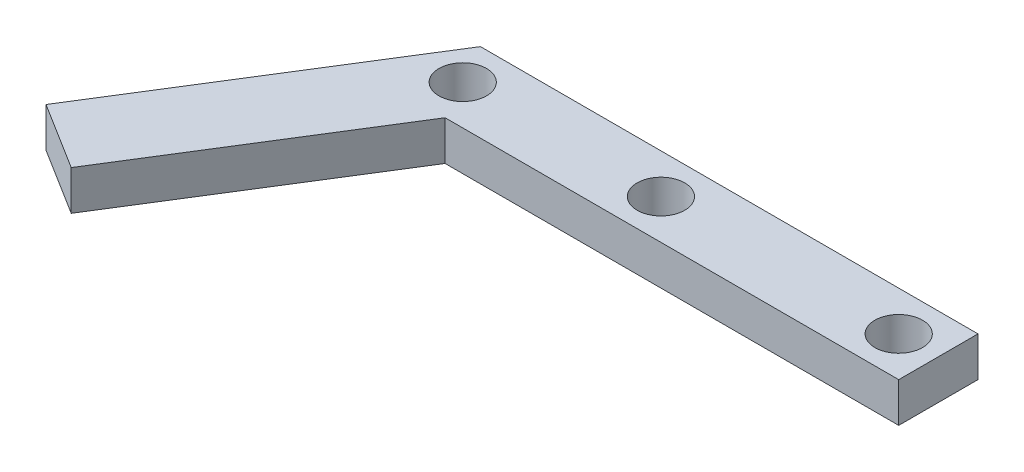
SolidWorks part; units mm, degrees
ref_plane "Front Plane" through (0, 0, 0) normal (0, 0, 1) x (1, 0, 0)
ref_plane "Top Plane" through (0, 0, 0) normal (0, 1, 0) x (1, 0, 0)
ref_plane "Right Plane" through (0, 0, 0) normal (1, 0, 0) x (0, 0, -1)
sketch "Sketch1" plane through (0, 0, 0) normal (0, 1, 0) x (1, 0, 0)
  line L0 (0, 0) -> (16.9574, 27.1375) construction
  line L1 (16.9574, 27.1375) -> (71.9574, 27.1375) construction
  line L2 (0, 0) -> (-2.6496, -4.2402) construction
  line L3 (1.5906, -6.8898) -> (-6.8898, -1.5906)
  line L4 (-6.8898, -1.5906) -> (14.1859, 32.1375)
  line L5 (1.5906, -6.8898) -> (19.729, 22.1375)
  line L6 (71.9574, 27.1375) -> (76.9574, 27.1375) construction
  line L7 (76.9574, 22.1375) -> (76.9574, 32.1375)
  line L8 (76.9574, 22.1375) -> (19.729, 22.1375)
  line L9 (76.9574, 32.1375) -> (14.1859, 32.1375)
  circle A1 centre (16.9574, 27.1375) radius 3
  circle A2 centre (71.9574, 27.1375) radius 3
  circle A3 centre (41.9574, 27.1375) radius 3
  point P13 (-2.6496, -4.2402)
  point P19 (76.9574, 27.1375)
  dimension "D4" = 5
  dimension "D1" = 122
  dimension "D2" = 55
  dimension "D3" = 32
  dimension "D5" = 10
  dimension "D6" = 5
  dimension "D7" = 10
  dimension "D8" = 30
extrude "Boss-Extrude2" add sketch "Sketch1" along normal mid plane 5
